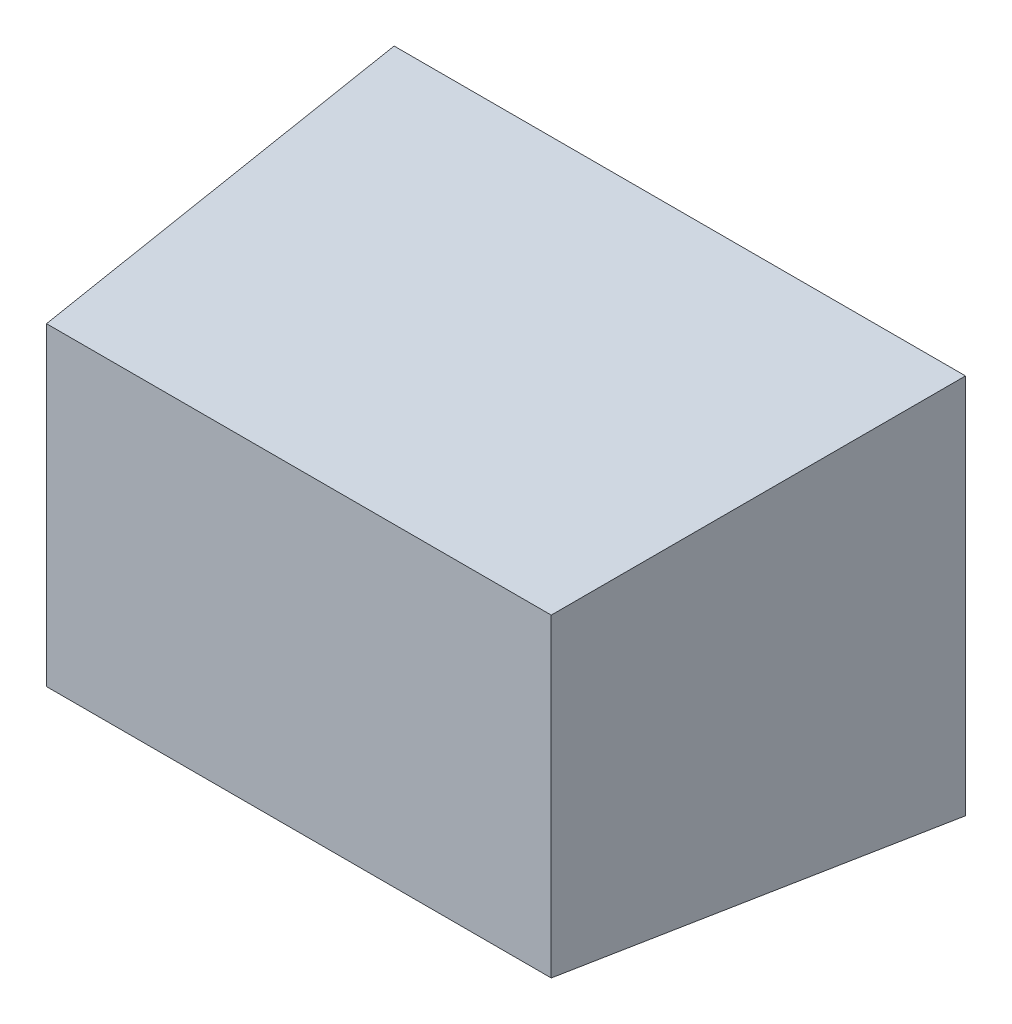
SolidWorks part; units mm, degrees
ref_plane "Front Plane" through (0, 0, 0) normal (0, 0, 1) x (1, 0, 0)
ref_plane "Top Plane" through (0, 0, 0) normal (0, 1, 0) x (1, 0, 0)
ref_plane "Right Plane" through (0, 0, 0) normal (1, 0, 0) x (0, 0, -1)
sketch "Sketch1" plane through (0, 0, 0) normal (0, 0, 1) x (1, 0, 0)
  line L1 (-75, 50) -> (75, 50)
  line L2 (-75, 50) -> (-75, -50)
  line L3 (-75, -50) -> (75, -50)
  line L4 (75, 50) -> (75, -50)
  line L5 (-75, 50) -> (75, -50) construction
  line L6 (-75, -50) -> (75, 50) construction
  point P0 (0, 0)
  point P6 (0, 0)
  dimension "D1" = 150
  dimension "D2" = 100
extrude "Boss-Extrude1" add sketch "Sketch1" along normal blind 100 draft 5
